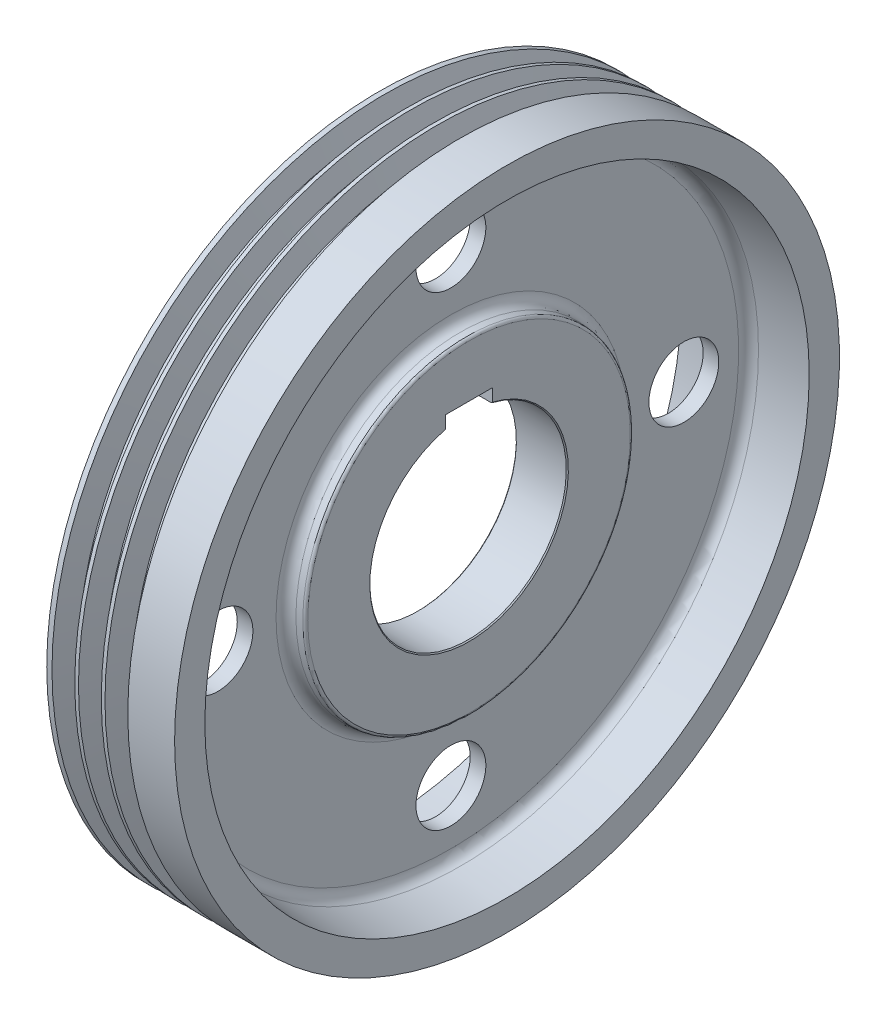
SolidWorks part; units mm, degrees
ref_plane "前视基准面" through (0, 0, 0) normal (0, 0, 1) x (1, 0, 0)
ref_plane "上视基准面" through (0, 0, 0) normal (0, 1, 0) x (1, 0, 0)
ref_plane "右视基准面" through (0, 0, 0) normal (1, 0, 0) x (0, 0, -1)
sketch "草图1" plane through (0, 0, 0) normal (0, 0, 1) x (1, 0, 0)
  line L0 (0, 0) -> (64.8368, 0) construction
  line L1 (36.5, 94.5) -> (36.5, 157.5)
  line L2 (0, 319.8) -> (123, 319.8)
  line L3 (123, 319.8) -> (123, 290.7)
  line L4 (36.5, 157.5) -> (7.5, 157.5) construction
  line L5 (54, 159.0311) -> (54, 285.9756)
  line L6 (86.5, 94.5) -> (36.5, 94.5)
  line L7 (5.0325, 319.8) -> (10.8719, 300.7) construction
  line L8 (10.8719, 300.7) -> (21.1281, 300.7) construction
  line L9 (21.1281, 300.7) -> (26.9675, 319.8) construction
  line L10 (0, 315) -> (123, 315) construction
  line L11 (16, 300.7) -> (16, 94.5) construction
  line L12 (44, 290.7) -> (0, 290.7) construction
  line L13 (123, 290.7) -> (79, 290.7) construction
  line L14 (69, 285.9756) -> (69, 159.0311)
  line L15 (42.5, 157.5) -> (86.5, 157.5) construction
  line L16 (61.5, 94.5) -> (61.5, 319.8) construction
  line L17 (86.5, 157.5) -> (86.5, 94.5)
  line L18 (0, 290.7) -> (0, 319.8)
  line L19 (54, 257.7) -> (69, 257.7) construction
  line L20 (54, 190.5) -> (69, 190.5) construction
  line L21 (123, 290.7) -> (123, 257.7) construction
  line L22 (123, 257.7) -> (69, 257.7) construction
  line L23 (69, 190.5) -> (86.5, 190.5) construction
  line L24 (86.5, 190.5) -> (86.5, 157.5) construction
  line L25 (69, 285.9756) -> (123, 290.7)
  line L26 (54, 285.9756) -> (0, 290.7)
  line L27 (54, 159.0311) -> (36.5, 157.5)
  line L28 (69, 159.0311) -> (86.5, 157.5)
  point P17 (6.5, 315)
  point P18 (25.5, 315)
  dimension "d2" = 581.4
  dimension "L" = 50
  dimension "B" = 123
  dimension "d" = 189
  dimension "d1" = 315
  dimension "D3" = 5
  dimension "D4" = 5
  dimension "dd" = 630
  dimension "f" = 16
  dimension "槽轮角" = 34
  dimension "bd" = 19
  dimension "hf" = 14.3
  dimension "ha" = 4.8
  dimension "da" = 639.6
  dimension "S" = 15
  dimension "S2" = 33
revolve "旋转1" add sketch "草图1" angle 360 about L0
sketch "草图2" plane through (0, 0, 0) normal (0, 0, 1) x (1, 0, 0)
  line L0 (21.1281, 300.7) -> (26.9675, 319.8) construction
  line L1 (10.8719, 300.7) -> (21.1281, 300.7) construction
  line L2 (5.0325, 319.8) -> (10.8719, 300.7) construction
  line L3 (21.1281, 300.7) -> (26.9675, 319.8)
  line L4 (10.8719, 300.7) -> (21.1281, 300.7)
  line L5 (5.0325, 319.8) -> (10.8719, 300.7)
  line L6 (5.0325, 319.8) -> (26.9675, 319.8)
  line L7 (0, 0) -> (123, 0) construction
revolve "切除-旋转1" cut sketch "草图2" angle 360 about L7
pattern_linear "轮槽数" count 3 spacing 25.5 along (1, 0, 0) of "切除-旋转1"
chamfer "倒角1" distance 1 2 edges at (36.5, 0, 94.5) (86.5, 0, 94.5)
sketch "草图4" plane through (36.5, 0, 0) normal (-1, 0, 0) x (0, 0, 1)
  line L1 (-22.5, 91.7824) -> (22.5, 91.7824)
  line L2 (-22.5, 91.7824) -> (-22.5, 104.9)
  line L3 (-22.5, 104.9) -> (22.5, 104.9)
  line L4 (22.5, 91.7824) -> (22.5, 104.9)
  circle A0 centre (0, 0) radius 94.5 construction
  point P6 (12.1, 104.9)
  dimension "键槽高度" = 104.9
  dimension "键槽宽度" = 45
  dimension "t1" = 10.4
extrude "切除-拉伸1" cut sketch "草图4" against normal through all
fillet "圆角1" radius 10 4 edges at (69, 0, 285.9756) (54, 0, 159.0311) (54, 0, 285.9756) (69, 0, 159.0311)
fillet "圆角2" radius 2.5 2 edges at (86.5, 0, 157.5) (36.5, 0, 157.5)
sketch "草图5" plane through (0, 0, 0) normal (1, 0, 0) x (0, 0, -1)
  line L0 (0, 300.7) -> (0, 94.5) construction
  circle A0 centre (0, 224.1) radius 33.6
extrude "切除-拉伸2" cut sketch "草图5" along normal through all
pattern_circular "圆孔个数" count 4 over 360 about axis through (0, 0, 0) along (1, 0, 0) of "切除-拉伸2"
